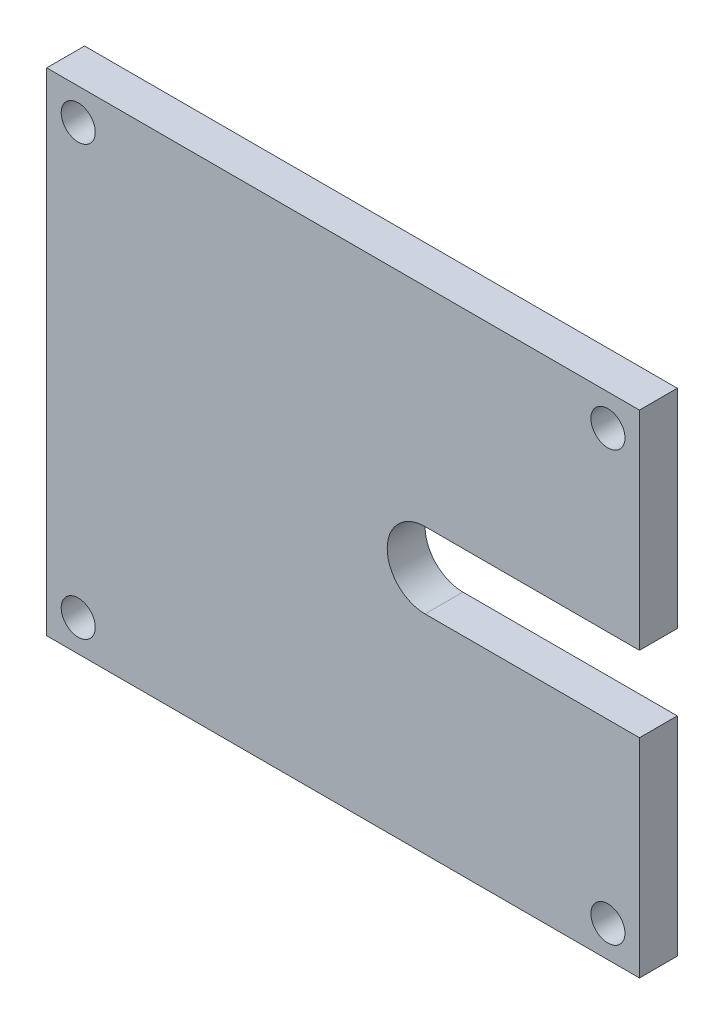
SolidWorks part; units mm, degrees
material "6061 合金"
ref_plane "前视基准面" through (0, 0, 0) normal (0, 0, 1) x (1, 0, 0)
ref_plane "上视基准面" through (0, 0, 0) normal (0, 1, 0) x (1, 0, 0)
ref_plane "右视基准面" through (0, 0, 0) normal (1, 0, 0) x (0, 0, -1)
sketch "草图1" plane through (0, 0, 0) normal (0, 0, 1) x (1, 0, 0)
  line L1 (-23.5, -19.5) -> (23.5, -19.5)
  line L2 (-23.5, -19.5) -> (-23.5, 19.5)
  line L3 (-23.5, 19.5) -> (23.5, 19.5)
  line L4 (23.5, -19.5) -> (23.5, 19.5)
  line L5 (-23.5, -19.5) -> (23.5, 19.5) construction
  line L6 (-23.5, 19.5) -> (23.5, -19.5) construction
  point P0 (0, 0)
  dimension "D1" = 47
  dimension "D2" = 39
extrude "凸台-拉伸1" add sketch "草图1" along normal blind 3
sketch "草图2" plane through (0, 0, 3) normal (0, 0, 1) x (1, 0, 0)
  line L1 (-21, -17) -> (21, -17)
  line L2 (-21, -17) -> (-21, 17)
  line L3 (-21, 17) -> (21, 17)
  line L4 (21, -17) -> (21, 17)
  line L5 (-21, -17) -> (21, 17) construction
  line L6 (-21, 17) -> (21, -17) construction
  line L7 (0, 0) -> (21, 0) construction
  line L9 (0, 0) -> (0, 17) construction
  point P2 (21, 17)
  point P5 (-21, -17)
  point P6 (-21, 17)
  point P7 (21, -17)
  dimension "D1" = 42
  dimension "D2" = 34
hole_wizard "M2.5 间隙孔1" positions "草图4" profile "草图3" hole size "M2.5" standard "GB" end condition up to next
sketch "草图4" plane through (0, 0, 3) normal (0, 0, 1) x (1, 0, 0)
  point P0 (-21, -17)
  point P3 (21, 17)
  point P6 (21, -17)
  point P9 (-21, 17)
sketch "草图3" plane through (-21, -17, 3) normal (1, 0, 0) x (0, -1, 0)
  line L0 (0, 0) -> (0, 3)
  line L1 (0, 3) -> (1.35, 3)
  line L2 (1.35, 3) -> (1.35, 0)
  line L5 (1.35, 0) -> (0, 0)
  line L11 (0, -6.35) -> (0, 107.95) construction
  dimension "通孔孔直径" = 2.7
  dimension "通孔孔深度" = 3
sketch "草图5" plane through (0, 0, 3) normal (0, 0, 1) x (1, 0, 0)
  line L0 (6.5, 0) -> (23.5, 0) construction
  line L1 (23.5, -19.5) -> (23.5, 19.5) construction
  line L2 (6.5, 3) -> (23.5, 3)
  line L3 (6.5, -3) -> (23.5, -3)
  arc A0 (6.5, 3) -> (6.5, -3) centre (6.5, 0) ccw
  arc A1 (23.5, -3) -> (23.5, 3) centre (23.5, 0) ccw
  point P4 (15, 0)
  dimension "D2" = 20
  dimension "D1" = 6
extrude "切除-拉伸1" cut sketch "草图5" against normal up to next
